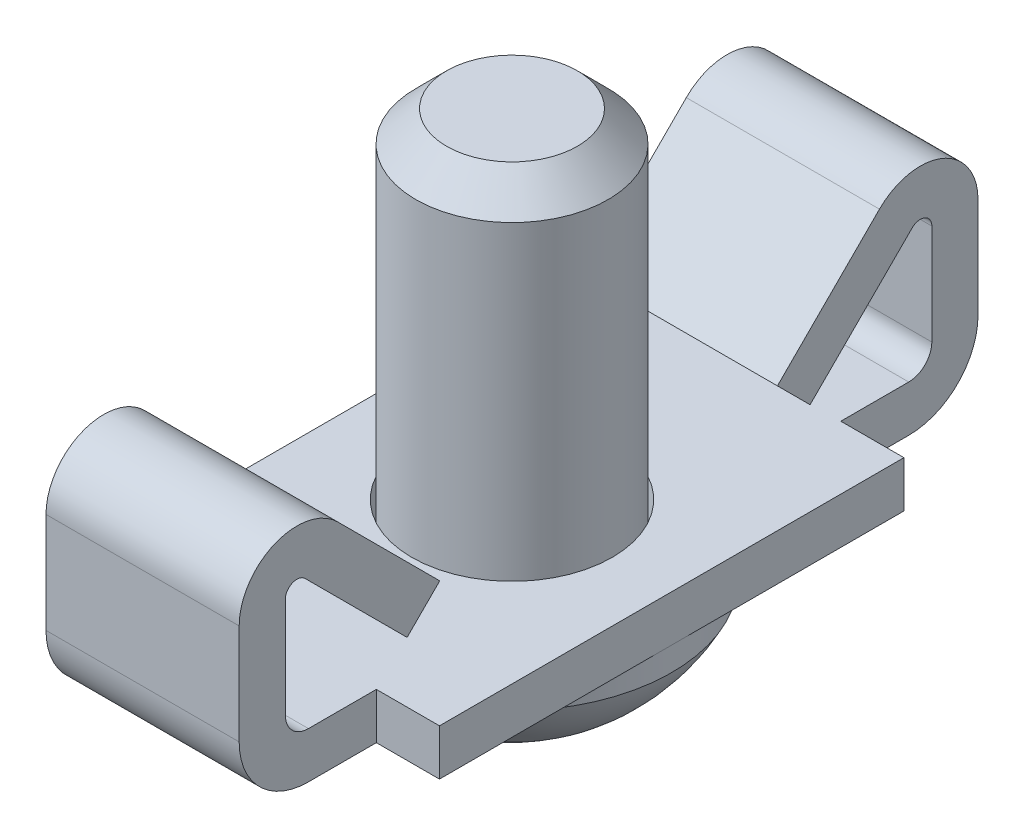
SolidWorks part; units mm, degrees
ref_plane "Front Plane" through (0, 0, 0) normal (0, 0, 1) x (1, 0, 0)
ref_plane "Top Plane" through (0, 0, 0) normal (0, 1, 0) x (1, 0, 0)
ref_plane "Right Plane" through (0, 0, 0) normal (1, 0, 0) x (0, 0, -1)
sketch "Sketch1" plane through (0, 0, 0) normal (1, 0, 0) x (0, 0, -1)
  line L0 (0, 0) -> (0, 52.3327) construction
  line L1 (9.906, 0) -> (-9.906, 0)
  line L2 (-12.192, 2.286) -> (-12.192, 5.6007)
  line L3 (12.192, 2.286) -> (12.192, 5.6007)
  line L4 (-8.94, 6.9477) -> (-5.5724, 3.5801)
  line L5 (8.94, 6.9477) -> (5.5724, 3.5801)
  line L6 (-5.5724, 3.5801) -> (-6.65, 2.5025)
  line L7 (5.5724, 3.5801) -> (6.65, 2.5025)
  line L8 (-6.65, 2.5025) -> (-10.0176, 5.8701)
  line L9 (6.65, 2.5025) -> (10.0176, 5.8701)
  line L10 (-10.668, 5.6007) -> (-10.668, 2.286)
  line L11 (10.668, 5.6007) -> (10.668, 2.286)
  line L12 (-9.906, 1.524) -> (9.906, 1.524)
  arc A0 (-9.906, 1.524) -> (-10.668, 2.286) centre (-9.906, 2.286) cw
  arc A1 (10.668, 2.286) -> (9.906, 1.524) centre (9.906, 2.286) cw
  arc A2 (10.668, 5.6007) -> (10.0176, 5.8701) centre (10.287, 5.6007) ccw
  arc A3 (-10.0176, 5.8701) -> (-10.668, 5.6007) centre (-10.287, 5.6007) ccw
  arc A4 (12.192, 2.286) -> (9.906, 0) centre (9.906, 2.286) cw
  arc A5 (-12.192, 2.286) -> (-9.906, 0) centre (-9.906, 2.286) ccw
  arc A6 (-8.94, 6.9477) -> (-12.192, 5.6007) centre (-10.287, 5.6007) ccw
  arc A7 (12.192, 5.6007) -> (8.94, 6.9477) centre (10.287, 5.6007) ccw
  point P17 (-10.668, 1.524)
  point P20 (10.668, 1.524)
  point P23 (10.668, 6.5205)
  point P26 (-10.668, 6.5205)
  point P29 (12.192, 0)
  point P32 (-12.192, 0)
  point P35 (-12.192, 10.1998)
  point P38 (12.192, 10.1998)
  dimension "D6" = 0.762
  dimension "D7" = 0.762
  dimension "D8" = 0.381
  dimension "D9" = 2.286
  dimension "D10" = 1.905
  dimension "D1" = 1.524
  dimension "D2" = 1.524
  dimension "D3" = 1.524
  dimension "D4" = 45
  dimension "D5" = 24.384
  dimension "D11" = 7.5057
  dimension "D12" = 4.7625
extrude "Boss-Extrude1" add sketch "Sketch1" along normal mid plane 6.3754
sketch "Sketch2" plane through (3.1877, 0, 0) normal (1, 0, 0) x (0, 0, -1)
  line L0 (0, 0) -> (0, 8.3162) construction
  line L1 (-9.906, 0) -> (9.906, 0) construction
  line L2 (-7.6645, 0) -> (7.6645, 0)
  line L3 (-7.6645, 0) -> (-7.6645, 1.524)
  line L4 (-7.6645, 1.524) -> (7.6645, 1.524)
  line L5 (7.6645, 0) -> (7.6645, 1.524)
  line L6 (9.906, 1.524) -> (-9.906, 1.524) construction
  dimension "D1" = 15.3289
extrude "Boss-Extrude2" add sketch "Sketch2" along normal blind 2.0828
mirror "Mirror1" about plane through (0, 0, 0) normal (1, 0, 0) of "Boss-Extrude2"
sketch "Sketch3" plane through (0, 1.524, 0) normal (0, 1, 0) x (1, 0, 0)
  circle A0 centre (0, 0) radius 3.3083
  dimension "D1" = 6.6167
extrude "Cut-Extrude1" cut sketch "Sketch3" against normal through all
sketch "Sketch4" plane through (0, 0, 0) normal (1, 0, 0) x (0, 0, -1)
  line L0 (3.175, 0) -> (5.2705, 0)
  line L1 (5.2705, 0) -> (5.2705, -0.7874)
  line L2 (0, -3.175) -> (3.175, -3.175)
  line L3 (0, 12.7) -> (0, -3.175)
  line L4 (3.175, 0) -> (3.175, 11.684)
  line L5 (3.175, 11.684) -> (2.159, 12.7)
  line L6 (2.159, 12.7) -> (0, 12.7)
  line L7 (0, 19.2607) -> (0, -7.2228) construction
  arc A0 (3.175, -3.175) -> (5.2705, -0.7874) centre (-0.3981, 2.0743) ccw
  point P11 (0, -1.524)
  point P12 (0, 0)
  dimension "D2" = 6.35
  dimension "D1" = 10.541
  dimension "D3" = 0.7874
  dimension "D4" = 6.35
revolve "Revolve1" add sketch "Sketch4" angle 360 about L7
sketch "Sketch5" plane through (0, -3.175, 0) normal (0, -1, 0) x (1, 0, 0)
  line L1 (0, 2.2877) -> (-1.9812, 1.1438)
  line L2 (-1.9812, 1.1438) -> (-1.9812, -1.1438)
  line L3 (-1.9812, -1.1438) -> (0, -2.2877)
  line L4 (0, -2.2877) -> (1.9812, -1.1438)
  line L5 (1.9812, -1.1438) -> (1.9812, 1.1438)
  line L6 (1.9812, 1.1438) -> (0, 2.2877)
  circle A0 centre (0, 0) radius 1.9812 construction
  dimension "D1" = 3.9624
extrude "Cut-Extrude2" cut sketch "Sketch5" against normal blind 3.175
